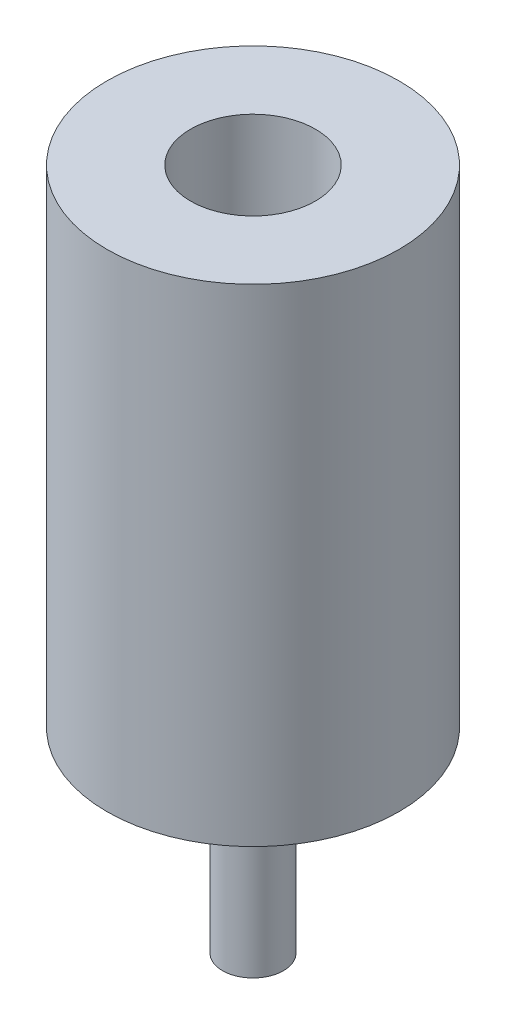
SolidWorks part; units mm, degrees
material "Copper"
ref_plane "Front Plane" through (0, 0, 0) normal (0, 0, 1) x (1, 0, 0)
ref_plane "Top Plane" through (0, 0, 0) normal (0, 1, 0) x (1, 0, 0)
ref_plane "Right Plane" through (0, 0, 0) normal (1, 0, 0) x (0, 0, -1)
sketch "Sketch1" plane through (0, 0, 0) normal (0, 1, 0) x (1, 0, 0)
  circle A0 centre (0, 0) radius 2.375
  dimension "D1" = 4.75
extrude "Boss-Extrude1" add sketch "Sketch1" along normal blind 7.92
sketch "Sketch3" plane through (0, 0, 0) normal (0, -1, 0) x (-1, 0, 0)
  circle A0 centre (0, 0) radius 0.495
  dimension "D1" = 0.99
extrude "Boss-Extrude2" add sketch "Sketch3" along normal blind 3.18
sketch "Sketch4" plane through (0, 7.92, 0) normal (0, 1, 0) x (1, 0, 0)
  circle A0 centre (0, 0) radius 1.015
  dimension "D1" = 2.03
extrude "Cut-Extrude1" cut sketch "Sketch4" against normal blind 6.35
